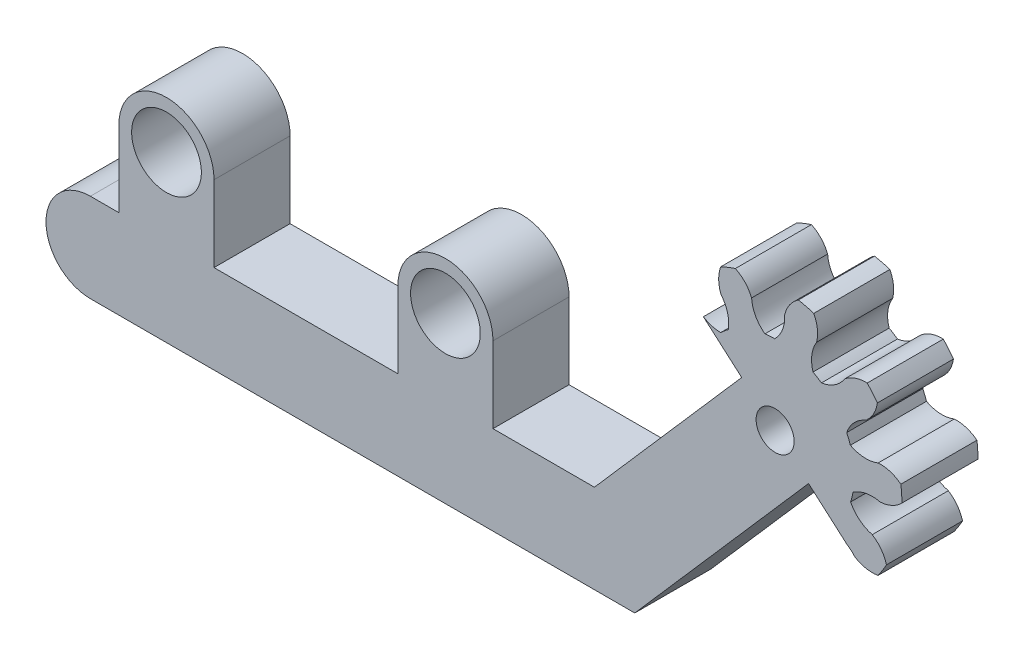
SolidWorks part; units mm, degrees
ref_plane "Alzado" through (0, 0, 0) normal (0, 0, 1) x (1, 0, 0)
ref_plane "Planta" through (0, 0, 0) normal (0, 1, 0) x (1, 0, 0)
ref_plane "Vista lateral" through (0, 0, 0) normal (1, 0, 0) x (0, 0, -1)
sketch "Croquis2" plane through (0, 0, 0) normal (0, 0, 1) x (1, 0, 0)
  line L9 (0, 0) -> (42.931, 0)
  line L11 (42.931, 0) -> (56.6365, 15.6981)
  line L12 (28, 13) -> (37.1706, 13) construction
  line L13 (2.25, 7) -> (0, 7)
  line L14 (2.25, 13) -> (2.25, 7)
  line L15 (9.75, 7) -> (9.75, 13)
  line L16 (24.25, 13) -> (24.25, 7)
  line L17 (31.75, 7) -> (31.75, 13)
  line L18 (51.3635, 20.3019) -> (39.75, 7)
  line L19 (24.25, 7) -> (9.75, 7)
  line L20 (39.75, 7) -> (31.75, 7)
  arc A6 (0, 7) -> (0, 0) centre (0, 3.5) ccw
  arc A7 (56.6365, 15.6981) -> (51.3635, 20.3019) centre (54, 18) ccw
  circle A8 centre (6, 13) radius 2.75
  circle A9 centre (28, 13) radius 2.75
  arc A10 (9.75, 13) -> (2.25, 13) centre (6, 13) ccw
  arc A11 (31.75, 13) -> (24.25, 13) centre (28, 13) ccw
  dimension "D2" = 7.5
  dimension "D7" = 5
  dimension "D1" = 6
  dimension "D10" = 5.5
  dimension "D11" = 5.5
  dimension "D3" = 7.5
  dimension "D4" = 22
  dimension "D5" = 7
  dimension "D6" = 26
  dimension "D8" = 7
  dimension "D9" = 6
  dimension "D12" = 8
extrude "Saliente-Extruir1" add sketch "Croquis2" along normal blind 6
sketch "Croquis3" plane through (0, 0, 6) normal (0, 0, 1) x (1, 0, 0)
  line L0 (51.3635, 20.3019) -> (56.6365, 15.6981) construction
  line L1 (51.3635, 20.3019) -> (46.467, 24.5768)
  line L2 (56.6365, 15.6981) -> (61.533, 11.4232)
  arc A0 (51.3635, 20.3019) -> (56.6365, 15.6981) centre (54, 18) cw
  arc A1 (46.467, 24.5768) -> (61.533, 11.4232) centre (54, 18) cw
  dimension "D1" = 10
extrude "Saliente-Extruir2" add sketch "Croquis3" against normal blind 6
sketch "Croquis4" plane through (0, 0, 6) normal (0, 0, 1) x (1, 0, 0)
  line L1 (47.7224, 23.4808) -> (48.342, 22.9398) construction
  line L2 (46.467, 24.5768) -> (51.3635, 20.3019) construction
  line L3 (54, 18) -> (50.303, 23.0396) construction
  line L4 (54, 18) -> (53.9712, 24.2501) construction
  arc A0 (49.7066, 27.0314) -> (45.884, 23.8421) centre (54, 18) ccw
  arc A2 (50.303, 23.0396) -> (49.7044, 22.5401) centre (54, 18) ccw
  arc A3 (61.533, 11.4232) -> (46.467, 24.5768) centre (54, 18) ccw construction
  arc A6 (47.7224, 23.4808) -> (49.7044, 22.5401) centre (49.7327, 25.158) ccw
  arc A7 (49.7066, 27.0314) -> (49.7327, 25.158) centre (52.1641, 26.1288) ccw
  arc A8 (55.8351, 27.8302) -> (50.8679, 27.4968) centre (54, 18) ccw
  arc A9 (50.303, 23.0396) -> (49.7327, 25.158) centre (47.7224, 23.4808) ccw
  arc A10 (52.1428, 26.1239) -> (50.8679, 27.4968) centre (49.714, 25.1468) ccw
  arc A11 (47.7224, 23.4808) -> (45.884, 23.8421) centre (46.3317, 21.2626) ccw
  arc A13 (52.1428, 26.1239) -> (53.1934, 24.1979) centre (54.755, 26.2992) ccw
  arc A14 (53.9712, 24.2501) -> (53.1934, 24.1979) centre (54, 18) ccw
  arc A15 (53.9712, 24.2501) -> (54.755, 26.2992) centre (52.1428, 26.1239) ccw
  arc A16 (55.8351, 27.8302) -> (54.755, 26.2992) centre (57.2927, 25.6554) ccw
  arc A17 (61.2626, 24.8742) -> (57.0482, 27.5241) centre (54, 18) ccw
  arc A18 (57.2726, 25.664) -> (57.0482, 27.5241) centre (54.7333, 26.3012) ccw
  arc A19 (57.2726, 25.664) -> (56.9905, 23.4884) centre (59.489, 24.2704) ccw
  arc A20 (57.6505, 23.0734) -> (56.9905, 23.4884) centre (54, 18) ccw
  arc A21 (57.6505, 23.0734) -> (59.489, 24.2704) centre (57.2726, 25.664) ccw
  arc A22 (61.2626, 24.8742) -> (59.489, 24.2704) centre (61.1636, 22.258) ccw
  arc A23 (63.9161, 19.2924) -> (62.0642, 23.9135) centre (54, 18) ccw
  arc A24 (61.1524, 22.2767) -> (62.0642, 23.9135) centre (59.4726, 24.2848) ccw
  arc A25 (61.1524, 22.2767) -> (59.6453, 20.6824) centre (62.1263, 19.8465) ccw
  arc A26 (59.9353, 19.9587) -> (59.6453, 20.6824) centre (54, 18) ccw
  arc A27 (59.9353, 19.9587) -> (62.1263, 19.8465) centre (61.1524, 22.2767) ccw
  arc A28 (63.9161, 19.2924) -> (62.1263, 19.8465) centre (62.2982, 17.2341) ccw
  arc A29 (62.782, 13.2171) -> (63.9999, 18.0441) centre (54, 18) ccw
  arc A30 (62.3002, 17.2558) -> (63.9999, 18.0441) centre (62.1215, 19.8678) ccw
  arc A31 (62.3002, 17.2558) -> (60.1438, 16.8519) centre (61.6597, 14.7173) ccw
  arc A32 (59.9531, 16.0959) -> (60.1438, 16.8519) centre (54, 18) ccw
  arc A33 (59.9531, 16.0959) -> (61.6597, 14.7173) centre (62.3002, 17.2558) ccw
  arc A34 (62.782, 13.2171) -> (61.6597, 14.7173) centre (60.2633, 12.5028) ccw
  arc A35 (58.2934, 8.9686) -> (62.116, 12.1579) centre (54, 18) ccw
  arc A36 (60.2776, 12.5192) -> (62.116, 12.1579) centre (61.6683, 14.7374) ccw
  arc A37 (60.2776, 12.5192) -> (58.2956, 13.4599) centre (58.2673, 10.842) ccw
  arc A38 (57.697, 12.9604) -> (58.2956, 13.4599) centre (54, 18) ccw
  arc A39 (57.697, 12.9604) -> (58.2673, 10.842) centre (60.2776, 12.5192) ccw
  arc A40 (58.2934, 8.9686) -> (58.2673, 10.842) centre (55.8359, 9.8712) ccw
  dimension "D1" = 6
  dimension "D2" = 36
  dimension "D3" = 5.2361
  dimension "D4" = 6.2502
extrude "Cortar-Extruir1" cut sketch "Croquis4" against normal through all
sketch "Croquis5" plane through (0, 0, 6) normal (0, 0, 1) x (1, 0, 0)
  circle A0 centre (54, 18) radius 1.5
  dimension "D1" = 3
extrude "Cortar-Extruir2" cut sketch "Croquis5" against normal through all
ref_plane "Plano1" through (54, 0, 0) normal (1, 0, 0) x (0, 0, -1)
sketch "Croquis7" plane through (0, 0, 6) normal (0, 0, 1) x (1, 0, 0)
  line L0 (52.5, 18) -> (55.5, 18) construction
  circle A0 centre (54, 18) radius 1.5 construction
sketch "Croquis8" plane through (54, 0, 0) normal (1, 0, 0) x (0, 0, -1)
  line L0 (-6, 18) -> (4.5025, 18) construction
  point P2 (0, 0)
  point P3 (4.5025, 18)
  point P5 (-6, 18)
